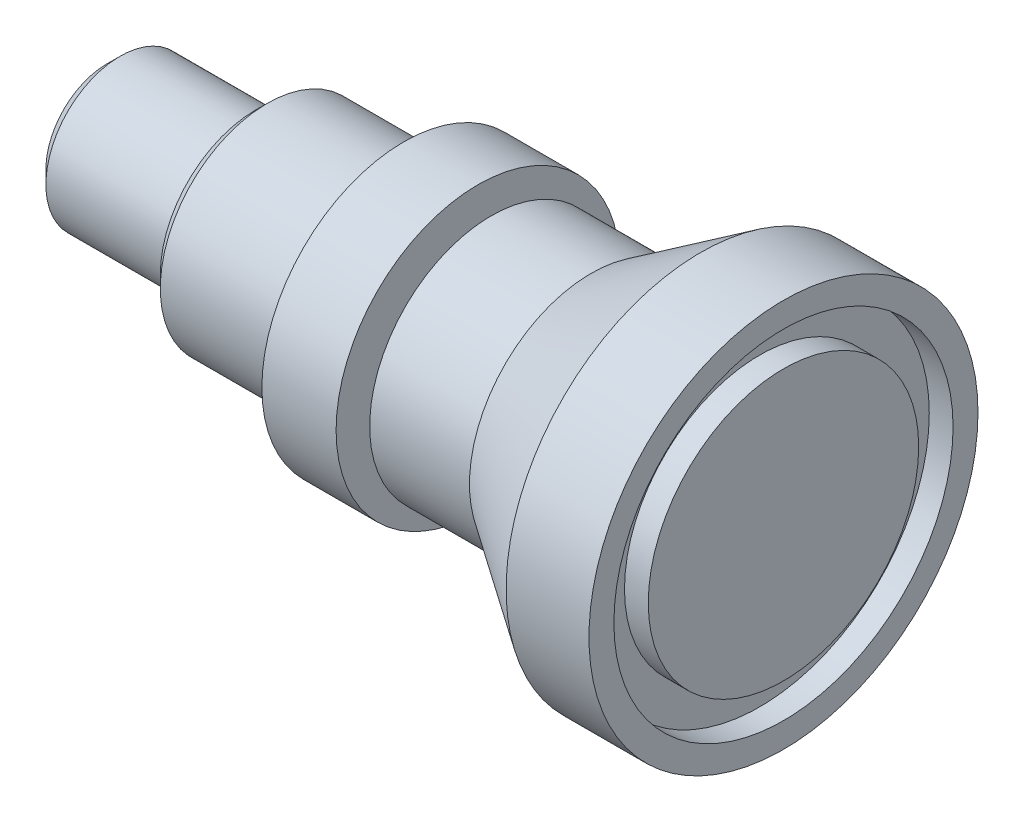
SolidWorks part; units mm, degrees
ref_plane "Front Plane" through (0, 0, 0) normal (0, 0, 1) x (1, 0, 0)
ref_plane "Top Plane" through (0, 0, 0) normal (0, 1, 0) x (1, 0, 0)
ref_plane "Right Plane" through (0, 0, 0) normal (1, 0, 0) x (0, 0, -1)
sketch "Sketch1" plane through (0, 0, 0) normal (0, 0, 1) x (1, 0, 0)
  line L0 (0, 0) -> (0, 2.6098)
  line L1 (0, 2.6098) -> (0.5652, 3.175)
  line L2 (0.5652, 3.175) -> (6.35, 3.175)
  line L3 (6.35, 3.175) -> (6.35, 4.0659)
  line L4 (6.35, 4.0659) -> (6.8561, 4.572)
  line L5 (6.8561, 4.572) -> (12.7, 4.572)
  line L6 (12.7, 4.572) -> (12.7, 6.0691)
  line L7 (12.7, 6.0691) -> (15.875, 6.0691)
  line L8 (15.875, 6.0691) -> (15.875, 3.175)
  line L9 (15.875, 3.175) -> (16.4476, 3.175)
  line L10 (16.4476, 3.175) -> (16.4476, 5.2049)
  line L11 (16.4476, 5.2049) -> (20.7157, 5.2049)
  line L12 (20.7157, 5.2049) -> (25.4017, 8.322)
  line L13 (25.4017, 8.322) -> (28.946, 8.322)
  line L14 (28.946, 8.322) -> (28.946, 7.2553)
  line L15 (28.946, 7.2553) -> (27.9283, 7.2553)
  line L16 (27.9283, 7.2553) -> (27.9283, 5.7848)
  line L17 (27.9283, 5.7848) -> (28.946, 5.7848)
  line L18 (28.946, 5.7848) -> (28.946, 0)
  line L19 (28.946, 0) -> (0, 0)
  point P8 (12.7, 5.3205)
  point P22 (6.35, 3.6204)
  dimension "D1" = 3.175
  dimension "D2" = 6.35
  dimension "D3" = 3.175
  dimension "D4" = 6.35
  dimension "D5" = 4.572
revolve "Revolve1" add sketch "Sketch1" angle 360 about L19
